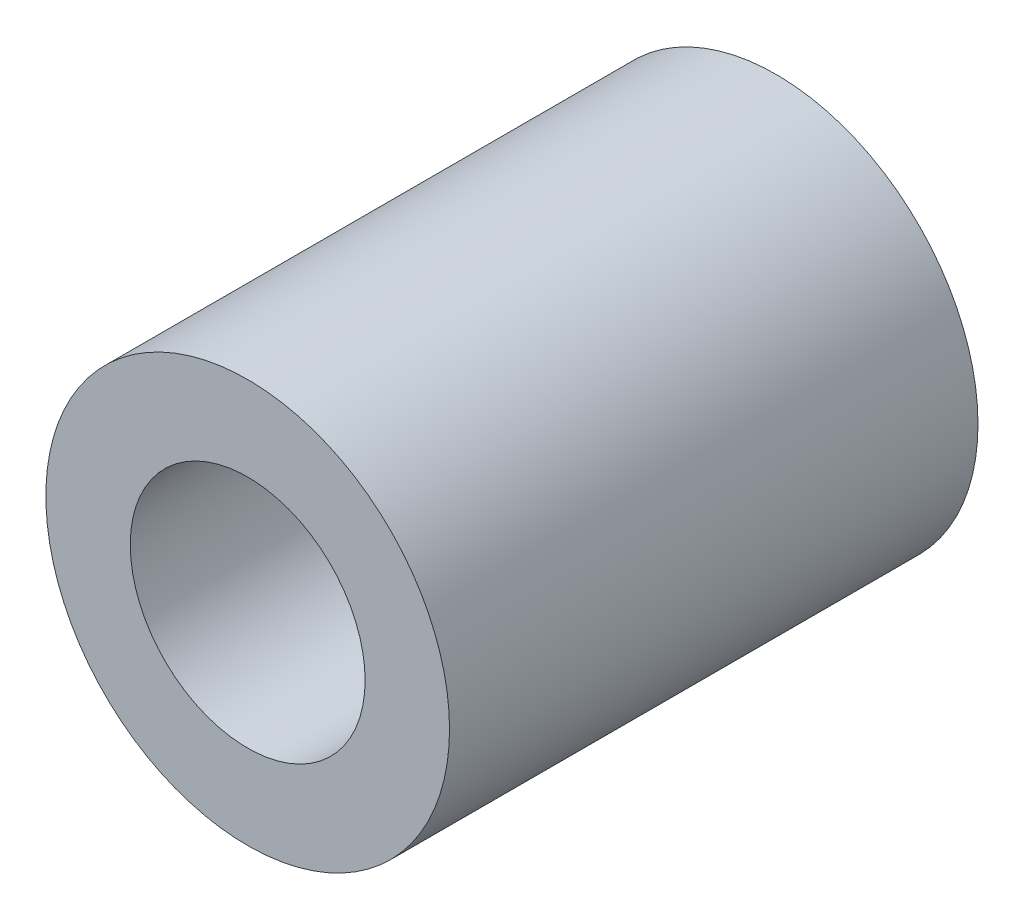
SolidWorks part; units mm, degrees
material "ABS"
ref_plane "正面" through (0, 0, 0) normal (0, 0, 1) x (1, 0, 0)
ref_plane "平面" through (0, 0, 0) normal (0, 1, 0) x (1, 0, 0)
ref_plane "右側面" through (0, 0, 0) normal (1, 0, 0) x (0, 0, -1)
sketch "ｽｹｯﾁ1" plane through (0, 0, 0) normal (0, 0, 1) x (1, 0, 0)
  circle A0 centre (0, 0) radius 1.6
  circle A1 centre (0, 0) radius 2.75
  dimension "D1" = 3.2
  dimension "D2" = 5.5
extrude "ﾎﾞｽ - 押し出し1" add sketch "ｽｹｯﾁ1" along normal blind 7.2
